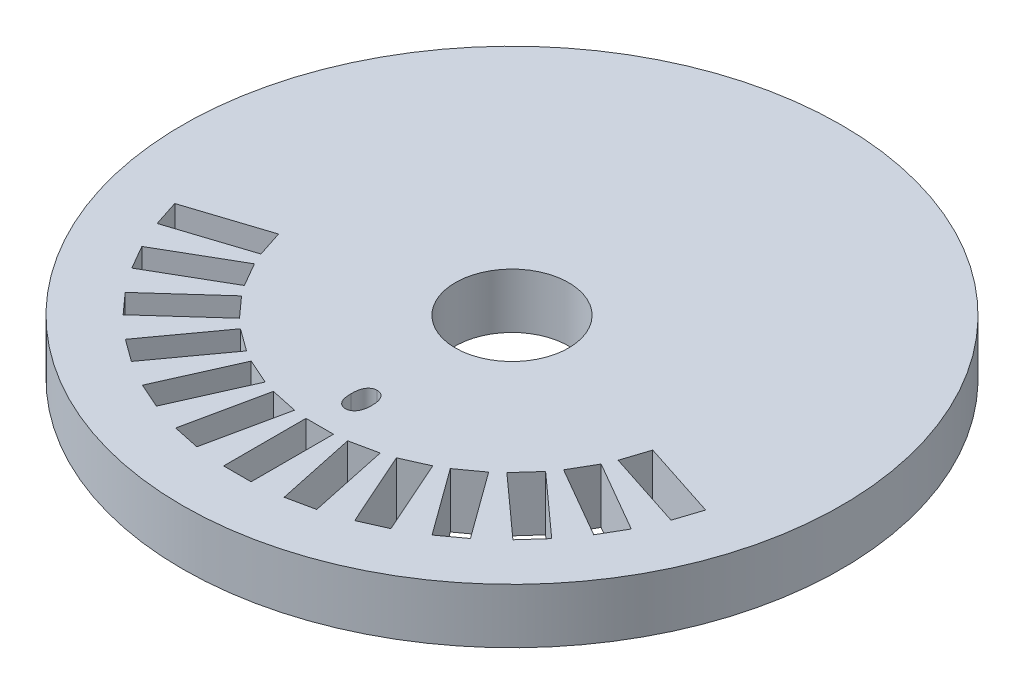
SolidWorks part; units mm, degrees
ref_plane "Front Plane" through (0, 0, 0) normal (0, 0, 1) x (1, 0, 0)
ref_plane "Top Plane" through (0, 0, 0) normal (0, 1, 0) x (1, 0, 0)
ref_plane "Right Plane" through (0, 0, 0) normal (1, 0, 0) x (0, 0, -1)
sketch "Sketch1" plane through (0, 0, 0) normal (0, 1, 0) x (1, 0, 0)
  circle A0 centre (0, 0) radius 6.55
  circle A1 centre (0, 0) radius 38.1
  dimension "D1" = 13.1
  dimension "D2" = 76.2
extrude "Boss-Extrude1" add sketch "Sketch1" along normal blind 6.35
sketch "Sketch2" plane through (0, 6.35, 0) normal (0, 1, 0) x (1, 0, 0)
  line L0 (0, 0) -> (0, -38.5632) construction
  line L1 (-6.1736, -21.4093) -> (-8.154, -30.7261)
  line L2 (-1.5875, -22.225) -> (1.5875, -22.225)
  line L3 (-1.5875, -22.225) -> (-1.5875, -31.75)
  line L4 (-1.5875, -31.75) -> (1.5875, -31.75)
  line L5 (1.5875, -22.225) -> (1.5875, -31.75)
  line L6 (0, -31.75) -> (0, -22.225) construction
  line L7 (-1.5875, -26.9875) -> (1.5875, -26.9875) construction
  line L8 (-6.1736, -21.4093) -> (-3.068, -22.0694)
  line L9 (-3.068, -22.0694) -> (-5.0484, -31.3862)
  line L10 (-8.154, -30.7261) -> (-5.0484, -31.3862)
  line L11 (0, 0) -> (-8.0177, -37.7205) construction
  line L12 (-10.49, -19.6579) -> (-14.3641, -28.3594)
  line L13 (-10.49, -19.6579) -> (-7.5895, -20.9492)
  line L14 (-7.5895, -20.9492) -> (-11.4636, -29.6508)
  line L15 (-14.3641, -28.3594) -> (-11.4636, -29.6508)
  line L16 (0, 0) -> (-15.6851, -35.2292) construction
  line L17 (-14.3478, -17.0473) -> (-19.9465, -24.7532)
  line L18 (-14.3478, -17.0473) -> (-11.7792, -18.9135)
  line L19 (-11.7792, -18.9135) -> (-17.3779, -26.6194)
  line L20 (-19.9465, -24.7532) -> (-17.3779, -26.6194)
  line L21 (0, 0) -> (-22.6669, -31.1983) construction
  line L22 (-17.5786, -13.6917) -> (-24.6571, -20.0652)
  line L23 (-17.5786, -13.6917) -> (-15.4541, -16.0512)
  line L24 (-15.4541, -16.0512) -> (-22.5326, -22.4246)
  line L25 (-24.6571, -20.0652) -> (-22.5326, -22.4246)
  line L26 (0, 0) -> (-28.658, -25.8038) construction
  line L27 (-20.0412, -9.7377) -> (-28.2901, -14.5002)
  line L28 (-20.0412, -9.7377) -> (-18.4537, -12.4873)
  line L29 (-18.4537, -12.4873) -> (-26.7026, -17.2498)
  line L30 (-28.2901, -14.5002) -> (-26.7026, -17.2498)
  line L31 (0, 0) -> (-33.3967, -19.2816) construction
  line L32 (-21.6278, -5.3581) -> (-30.6866, -8.3015)
  line L33 (-21.6278, -5.3581) -> (-20.6467, -8.3777)
  line L34 (-20.6467, -8.3777) -> (-29.7055, -11.3211)
  line L35 (-30.6866, -8.3015) -> (-29.7055, -11.3211)
  line L36 (0, 0) -> (-36.6758, -11.9167) construction
  line L37 (0, 0) -> (-1.5875, -22.225) construction
  line L38 (0, 0) -> (-6.1736, -21.4093) construction
  line L39 (3.068, -22.0694) -> (5.0484, -31.3862)
  line L40 (3.068, -22.0694) -> (6.1736, -21.4093)
  line L41 (6.1736, -21.4093) -> (8.154, -30.7261)
  line L42 (5.0484, -31.3862) -> (8.154, -30.7261)
  line L43 (0, 0) -> (8.0177, -37.7205) construction
  line L44 (7.5895, -20.9492) -> (11.4636, -29.6508)
  line L45 (7.5895, -20.9492) -> (10.49, -19.6579)
  line L46 (10.49, -19.6579) -> (14.3641, -28.3594)
  line L47 (11.4636, -29.6508) -> (14.3641, -28.3594)
  line L48 (0, 0) -> (15.6851, -35.2292) construction
  line L49 (11.7792, -18.9135) -> (17.3779, -26.6194)
  line L50 (11.7792, -18.9135) -> (14.3478, -17.0473)
  line L51 (14.3478, -17.0473) -> (19.9465, -24.7532)
  line L52 (17.3779, -26.6194) -> (19.9465, -24.7532)
  line L53 (0, 0) -> (22.6669, -31.1983) construction
  line L54 (15.4541, -16.0512) -> (22.5326, -22.4246)
  line L55 (15.4541, -16.0512) -> (17.5786, -13.6917)
  line L56 (17.5786, -13.6917) -> (24.6571, -20.0652)
  line L57 (22.5326, -22.4246) -> (24.6571, -20.0652)
  line L58 (0, 0) -> (28.658, -25.8038) construction
  line L59 (18.4537, -12.4873) -> (26.7026, -17.2498)
  line L60 (18.4537, -12.4873) -> (20.0412, -9.7377)
  line L61 (20.0412, -9.7377) -> (28.2901, -14.5002)
  line L62 (26.7026, -17.2498) -> (28.2901, -14.5002)
  line L63 (0, 0) -> (33.3967, -19.2816) construction
  line L64 (20.6467, -8.3777) -> (29.7055, -11.3211)
  line L65 (20.6467, -8.3777) -> (21.6278, -5.3581)
  line L66 (21.6278, -5.3581) -> (30.6866, -8.3015)
  line L67 (29.7055, -11.3211) -> (30.6866, -8.3015)
  line L68 (0, 0) -> (36.6758, -11.9167) construction
  line L69 (0, 0) -> (-1.5875, -22.225) construction
  line L70 (0, 0) -> (3.068, -22.0694) construction
  circle A0 centre (0, 0) radius 38.1 construction
  text T0 "\r\n0"
  point P4 (0, -26.9875)
  dimension "D1" = 3.175
  dimension "D2" = 9.525
  dimension "D3" = 22.225
  dimension "D5" = 12
  dimension "D7" = 12
  dimension "D4" = 7
  dimension "D6" = 7
extrude "Cut-Extrude1" cut sketch "Sketch2" against normal through all
delete or keep bodies "Body-Delete/Keep 1" type delete bodies bodies 103
sketch "Sketch3" plane through (0, 0, 0) normal (0, 1, 0) x (1, 0, 0)
  line L4 (-33.1549, 3.4847) -> (-11.2505, 1.1825)
  line L5 (11.2505, 1.1825) -> (33.1549, 3.4847)
  line L6 (30.6866, -8.3015) -> (21.6278, -5.3581) construction
  line L7 (-21.6278, -5.3581) -> (-30.6866, -8.3015) construction
  circle A5 centre (0, 0) radius 33.3375
  circle A6 centre (0, 0) radius 33.3375
  circle A8 centre (0, 0) radius 11.3125
  circle A9 centre (0, 0) radius 11.3125
  dimension "D3" = 24
  dimension "D4" = 24
  dimension "D1" = 4.7625
  dimension "D2" = 4.7625
extrude "Cut-Extrude2" cut sketch "Sketch3" along normal blind 3.175 contours L5 A9 L4 A6
